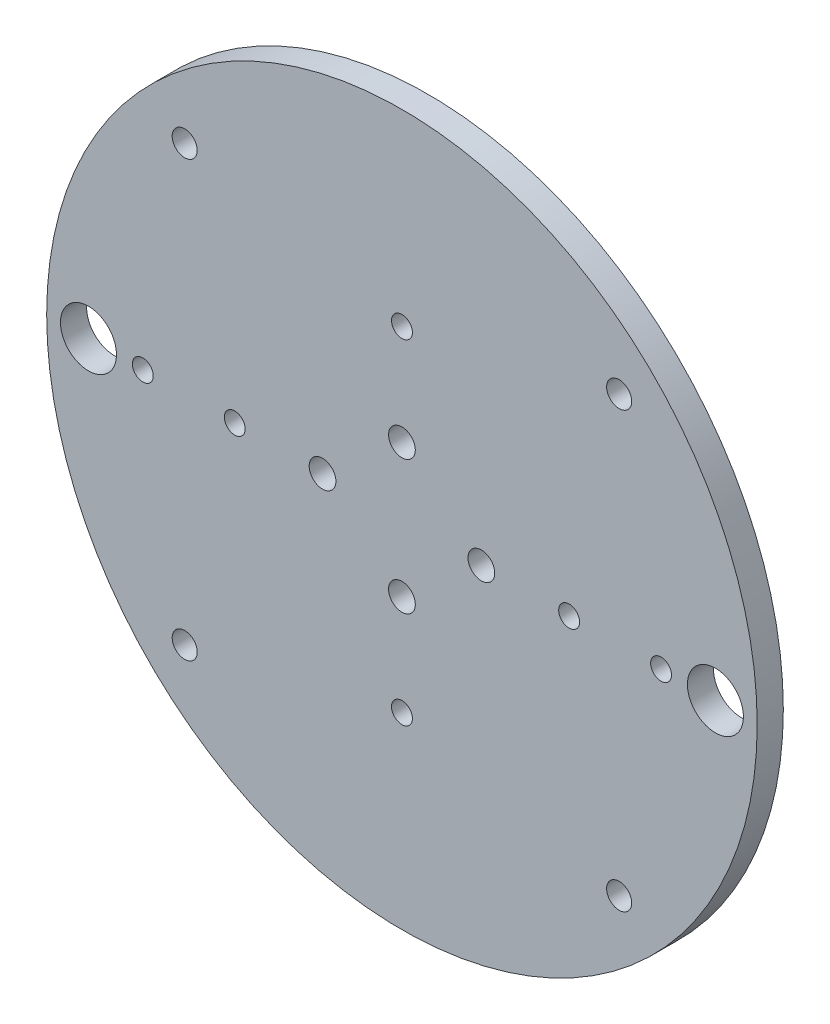
SolidWorks part; units mm, degrees
ref_plane "Front Plane" through (0, 0, 0) normal (0, 0, 1) x (1, 0, 0)
ref_plane "Top Plane" through (0, 0, 0) normal (0, 1, 0) x (1, 0, 0)
ref_plane "Right Plane" through (0, 0, 0) normal (1, 0, 0) x (0, 0, -1)
sketch "Sketch1" plane through (0, 0, 0) normal (0, 0, 1) x (1, 0, 0)
  circle A0 centre (0, 0) radius 42.5
  dimension "D1" = 85
extrude "Boss-Extrude1" add sketch "Sketch1" along normal blind 3.125
sketch "Sketch2" plane through (0, 0, 0) normal (0, 0, -1) x (-1, 0, 0)
  circle A0 centre (25.9862, -25.9862) radius 1.5 construction
  circle A1 centre (-25.9862, -25.9862) radius 1.5 construction
  circle A2 centre (25.9862, 25.9862) radius 1.5 construction
  circle A3 centre (-25.9862, 25.9862) radius 1.5 construction
  circle A4 centre (25.9862, -25.9862) radius 1.5
  circle A5 centre (-25.9862, -25.9862) radius 1.5
  circle A6 centre (25.9862, 25.9862) radius 1.5
  circle A7 centre (-25.9862, 25.9862) radius 1.5
extrude "Cut-Extrude1" cut sketch "Sketch2" against normal through all
sketch "Sketch3" plane through (0, 0, 3.125) normal (0, 0, 1) x (1, 0, 0)
  circle A0 centre (0, 20) radius 1.25
  circle A1 centre (0, 0) radius 20 construction
  circle A2 centre (20, 0) radius 1.25
  circle A3 centre (0, -20) radius 1.25
  circle A4 centre (-20, 0) radius 1.25
  point P15 (0, 0)
  dimension "D1" = 2.5
  dimension "D3" = 40
  dimension "D2" = 4
extrude "Cut-Extrude2" cut sketch "Sketch3" against normal through all
sketch "Sketch6" plane through (0, 0, 3.125) normal (0, 0, 1) x (1, 0, 0)
  circle A0 centre (-9.5, 0) radius 1.5 construction
  circle A1 centre (0, -8) radius 1.5 construction
  circle A2 centre (9.5, 0) radius 1.5 construction
  circle A3 centre (0, 8) radius 1.5 construction
  circle A4 centre (-9.5, 0) radius 1.5 construction
  circle A5 centre (0, -8) radius 1.5 construction
  circle A6 centre (9.5, 0) radius 1.5 construction
  circle A7 centre (0, 8) radius 1.5 construction
  circle A8 centre (-9.5, 0) radius 1.6
  circle A9 centre (0, 8) radius 1.6
  circle A10 centre (9.5, 0) radius 1.6
  circle A11 centre (0, -8) radius 1.6
  dimension "D1" = 3.2
extrude "Cut-Extrude3" cut sketch "Sketch6" against normal through all
sketch "Sketch7" plane through (0, 0, 0) normal (0, 0, -1) x (-1, 0, 0)
  arc A0 (37.675, -3.2453) -> (37.675, 3.2453) centre (37.5, 0) ccw construction
  arc A1 (-37.675, 3.2453) -> (-37.675, -3.2453) centre (-37.5, 0) ccw construction
  arc A2 (37.675, -3.2453) -> (37.675, 3.2453) centre (37.5, 0) ccw construction
  arc A3 (-37.675, 3.2453) -> (-37.675, -3.2453) centre (-37.5, 0) ccw construction
  circle A4 centre (37.5, 0) radius 3.35
  circle A5 centre (-37.5, 0) radius 3.35
  circle A6 centre (31, 0) radius 1.6 construction
  circle A7 centre (-31, 0) radius 1.6 construction
  circle A8 centre (31, 0) radius 1.6 construction
  circle A9 centre (-31, 0) radius 1.6 construction
  circle A10 centre (-31, 0) radius 1.25
  circle A11 centre (31, 0) radius 1.25
  dimension "D1" = 0.1
  dimension "D2" = 2.5
extrude "Cut-Extrude4" cut sketch "Sketch7" against normal through all
